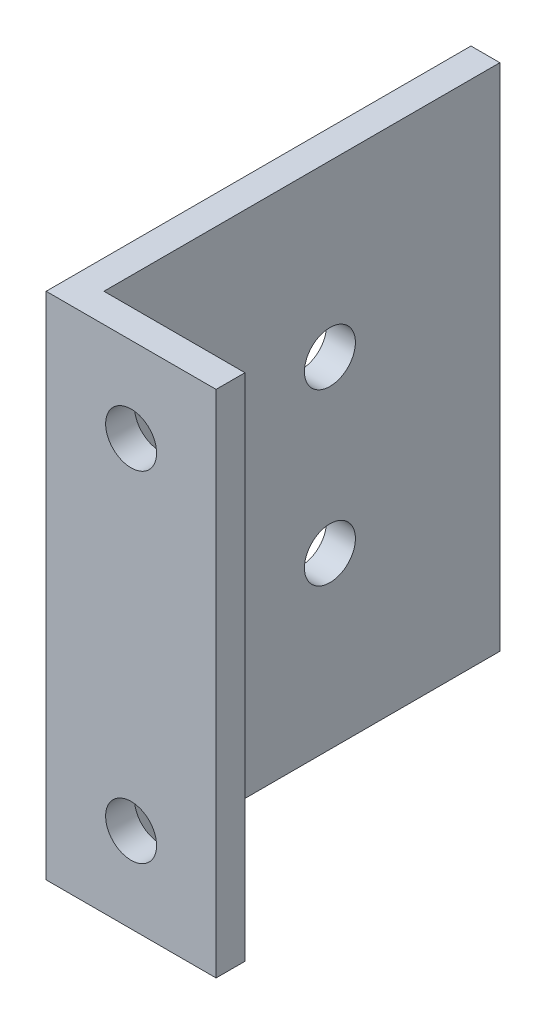
SolidWorks part; units mm, degrees
material "6061 Alloy"
ref_plane "Front Plane" through (0, 0, 0) normal (0, 0, 1) x (1, 0, 0)
ref_plane "Top Plane" through (0, 0, 0) normal (0, 1, 0) x (1, 0, 0)
ref_plane "Right Plane" through (0, 0, 0) normal (1, 0, 0) x (0, 0, -1)
sketch "Sketch9" plane through (0, 0, 0) normal (0, 1, 0) x (1, 0, 0)
  line L0 (0, 25) -> (0, 0)
  line L2 (0, -55) -> (0, 55) construction
  line L3 (0, 0) -> (25, 0)
  line L4 (-55, 0) -> (55, 0) construction
  dimension "D1" = 25
  dimension "D2" = 25
extrude "Extrude-Thin1" add sketch "Sketch9" along normal blind 30 thin thin type one direction reverse wall 1.7
sketch "Sketch10" plane through (0, 0, 0) normal (0, 0, 1) x (1, 0, 0)
  line L0 (0, 30) -> (25, 30) construction
  line L1 (0, -13.75) -> (0, 13.75) construction
  circle A0 centre (5, 25) radius 1.5
  circle A1 centre (5, 5) radius 1.5
  dimension "D1" = 3
  dimension "D2" = 5
  dimension "D3" = 20
  dimension "D4" = 5
extrude "Cut-Extrude1" cut sketch "Sketch10" against normal blind 10
sketch "Sketch11" plane through (0, 0, 0) normal (-1, 0, 0) x (0, 0, 1)
  line L1 (0, -13.75) -> (0, 13.75) construction
  line L2 (-25, 15) -> (0, 15) construction
  line L3 (-25, 30) -> (-25, 0) construction
  circle A0 centre (-15, 10) radius 1.5
  circle A1 centre (-15, 20) radius 1.5
  dimension "D1" = 5
  dimension "D2" = 10
  dimension "D3" = 15
  dimension "D4" = 3
extrude "Cut-Extrude2" cut sketch "Sketch11" against normal blind 10
sketch "Sketch12" plane through (0, 30, 0) normal (0, 1, 0) x (1, 0, 0)
  line L0 (-13.75, 0) -> (13.75, 0) construction
  line L1 (25, 1.7) -> (10, 1.7)
  line L2 (25, 1.7) -> (25, 0)
  line L3 (25, 0) -> (10, 0)
  line L4 (10, 1.7) -> (10, 0)
  dimension "D1" = 15
extrude "Cut-Extrude3" cut sketch "Sketch12" against normal blind 40
